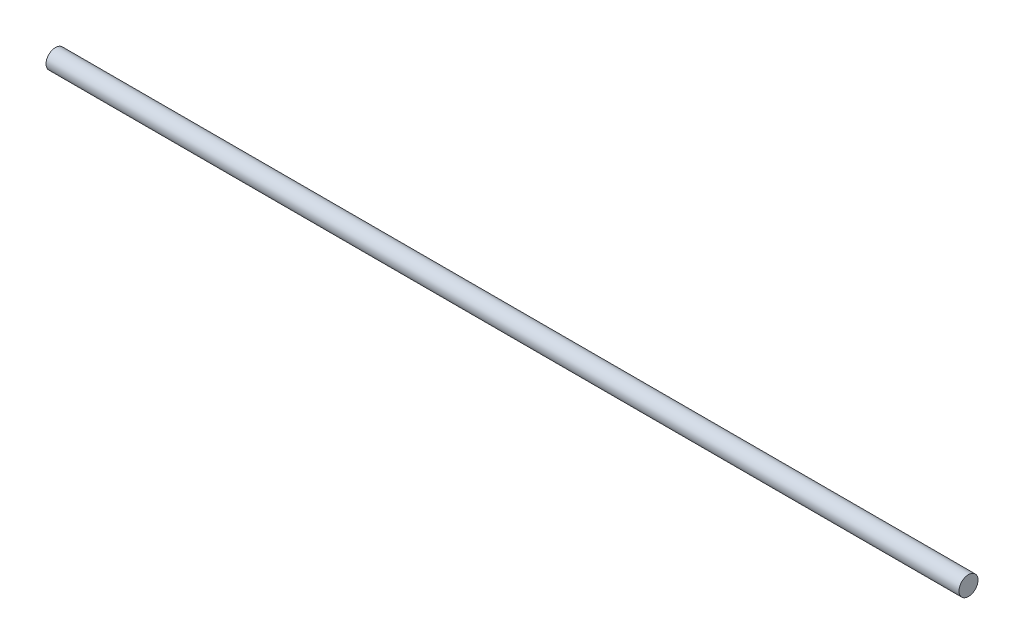
SolidWorks part; units mm, degrees
material "1023 Carbon Steel Sheet (SS)"
ref_plane "Front Plane" through (0, 0, 0) normal (0, 0, 1) x (1, 0, 0)
ref_plane "Top Plane" through (0, 0, 0) normal (0, 1, 0) x (1, 0, 0)
ref_plane "Right Plane" through (0, 0, 0) normal (1, 0, 0) x (0, 0, -1)
sketch "Sketch1" plane through (0, 0, 0) normal (1, 0, 0) x (0, 0, -1)
  circle A0 centre (0, 0) radius 3.175
  dimension "D1" = 6.35
extrude "Boss-Extrude1" add sketch "Sketch1" along normal blind 304.8
